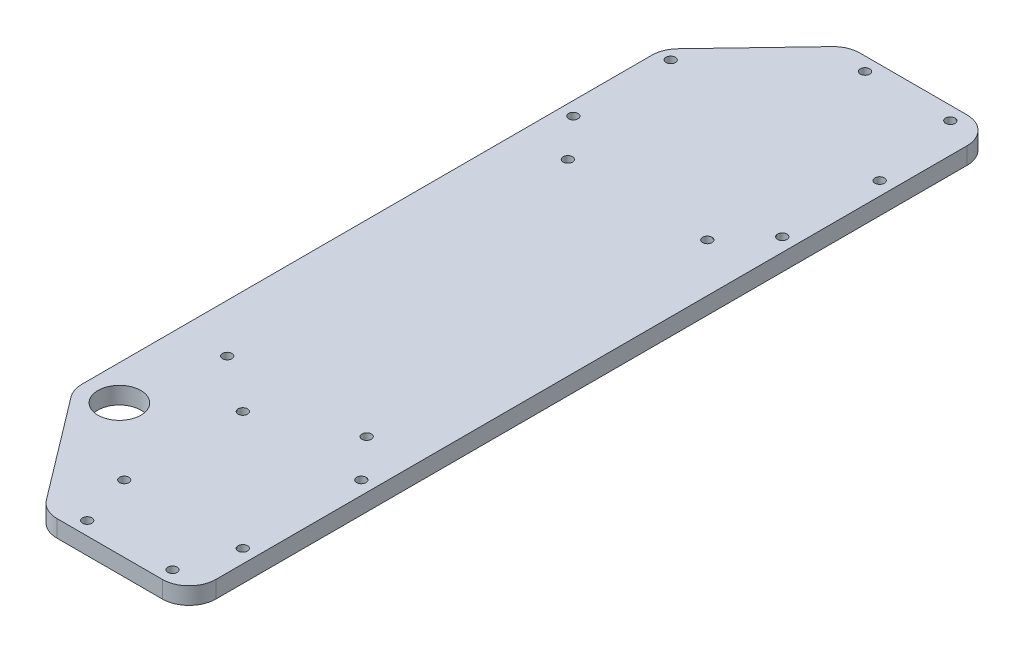
SolidWorks part; units mm, degrees
ref_plane "Front Plane" through (0, 0, 0) normal (0, 0, 1) x (1, 0, 0)
ref_plane "Top Plane" through (0, 0, 0) normal (0, 1, 0) x (1, 0, 0)
ref_plane "Right Plane" through (0, 0, 0) normal (1, 0, 0) x (0, 0, -1)
sketch "Sketch1" plane through (0, 0, 0) normal (0, 1, 0) x (1, 0, 0)
  line L0 (45, 295) -> (76.8, 295) construction
  line L1 (0, 0) -> (88, 0)
  line L2 (0, 0) -> (0, 300)
  line L3 (0, 300) -> (88, 300)
  line L4 (88, 0) -> (88, 300)
  line L5 (18, 211.2) -> (70, 211.2) construction
  line L6 (18, 211.2) -> (18, 84.2) construction
  line L7 (18, 84.2) -> (70, 84.2) construction
  line L8 (70, 211.2) -> (70, 84.2) construction
  line L9 (38.8, 69.2) -> (83, 69.2) construction
  line L10 (38.8, 69.2) -> (38.8, 25) construction
  line L11 (38.8, 25) -> (83, 25) construction
  line L12 (83, 69.2) -> (83, 25) construction
  line L13 (5.05, 226.2) -> (82.95, 226.2) construction
  line L14 (5.05, 226.2) -> (5.05, 262.5) construction
  line L15 (5.05, 262.5) -> (82.95, 262.5) construction
  line L16 (82.95, 226.2) -> (82.95, 262.5) construction
  line L17 (45, 5) -> (76.8, 5) construction
  line L18 (38.8, 25) -> (45, 5) construction
  line L19 (76.8, 5) -> (83, 25) construction
  line L20 (33.8, 0) -> (0, 44.6331)
  line L21 (33.8, 300) -> (0, 264.5204)
  line L22 (13, 49) -> (0, 49) construction
  line L23 (13, 49) -> (2.6364, 41.1518) construction
  line L24 (5.05, 262.5) -> (0, 262.5) construction
  line L25 (5.05, 262.5) -> (1.3936, 265.9833) construction
  circle A0 centre (18, 211.2) radius 1.75
  circle A1 centre (70, 84.2) radius 1.75
  circle A2 centre (18, 84.2) radius 1.75
  circle A3 centre (70, 211.2) radius 1.75
  circle A4 centre (5.05, 262.5) radius 1.75
  circle A5 centre (5.05, 226.2) radius 1.75
  circle A6 centre (82.95, 226.2) radius 1.75
  circle A7 centre (82.95, 262.5) radius 1.75
  circle A8 centre (38.8, 69.2) radius 1.75
  circle A9 centre (83, 69.2) radius 1.75
  circle A10 centre (83, 25) radius 1.75
  circle A11 centre (38.8, 25) radius 1.75
  circle A12 centre (45, 295) radius 1.75
  circle A13 centre (76.8, 295) radius 1.75
  circle A14 centre (45, 5) radius 1.75
  circle A15 centre (76.8, 5) radius 1.75
  circle A16 centre (13, 49) radius 8
  dimension "D3" = 3.5
  dimension "D14" = 3.5
  dimension "D21" = 16
  dimension "D1" = 88
  dimension "D2" = 300
  dimension "D4" = 52
  dimension "D5" = 127
  dimension "D6" = 18
  dimension "D7" = 77.9
  dimension "D8" = 36.3
  dimension "D9" = 44.2
  dimension "D11" = 5.05
  dimension "D12" = 15
  dimension "D13" = 15
  dimension "D10" = 5
  dimension "D15" = 5
  dimension "D16" = 11.2
  dimension "D18" = 5
  dimension "D17" = 31.8
  dimension "D19" = 11.2
  dimension "D20" = 20
  dimension "D22" = 13
  dimension "D23" = 49
  dimension "D24" = 11.2
  dimension "D25" = 11.2
extrude "Boss-Extrude1" add sketch "Sketch1" along normal blind 6.35 contours L20 L1 L4 L3 L2 A16 A15 A14 A13 A12 A11 A10 A9 A8 A7 A6 A5 A4 A3 A2 A1 A0
fillet "Fillet1" radius 10 6 edges at (88, 3.175, -300) (88, 3.175, 0) (33.8, 3.175, 0) (0, 3.175, -44.6331) (33.8, 3.175, -300) (0, 3.175, -264.5204)
equation "\"D16@Sketch1\"=\"D19@Sketch1\""
equation "\"D24@Sketch1\"=\"D19@Sketch1\""
equation "\"D13@Sketch1\"=\"D12@Sketch1\""
equation "\"D25@Sketch1\"=\"D19@Sketch1\""
